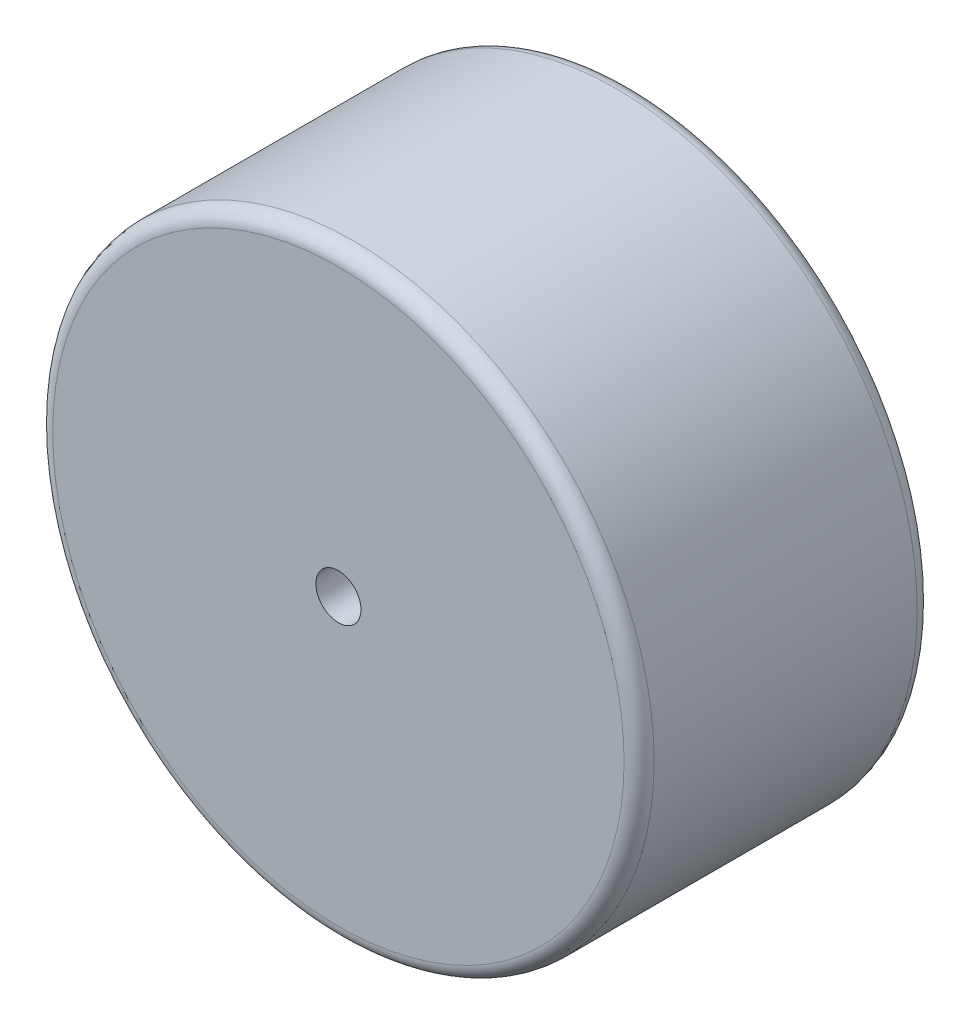
SolidWorks part; units mm, degrees
ref_plane "前视基准面" through (0, 0, 0) normal (0, 0, 1) x (1, 0, 0)
ref_plane "上视基准面" through (0, 0, 0) normal (0, 1, 0) x (1, 0, 0)
ref_plane "右视基准面" through (0, 0, 0) normal (1, 0, 0) x (0, 0, -1)
sketch "草图1" plane through (0, 0, 0) normal (0, 0, 1) x (1, 0, 0)
  circle A0 centre (0, 0) radius 20
  dimension "D1" = 40
extrude "凸台-拉伸1" add sketch "草图1" along normal blind 19.5
fillet "圆角1" radius 1 2 edges at (20, 0, 0) (20, 0, 19.5)
sketch "草图2" plane through (0, 0, 19.5) normal (0, 0, 1) x (1, 0, 0)
  circle A0 centre (0, 0) radius 1.5
  dimension "D1" = 3
extrude "切除-拉伸1" cut sketch "草图2" against normal blind 20
